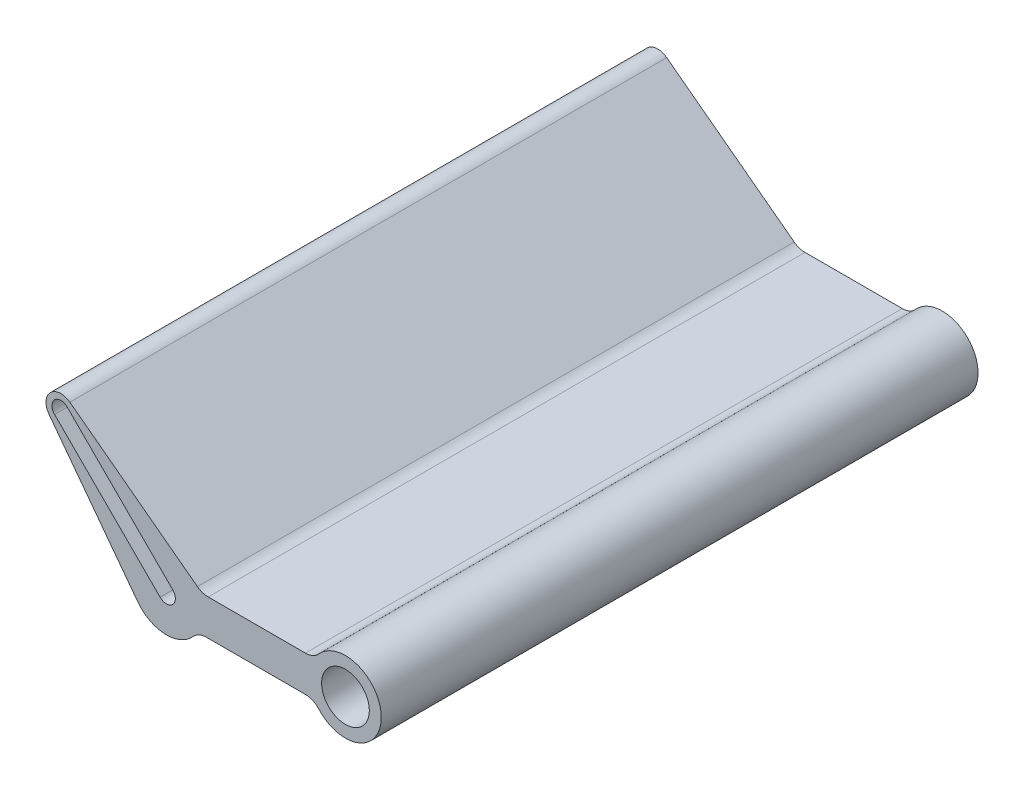
SolidWorks part; units mm, degrees
ref_plane "Front Plane" through (0, 0, 0) normal (0, 0, 1) x (1, 0, 0)
ref_plane "Top Plane" through (0, 0, 0) normal (0, 1, 0) x (1, 0, 0)
ref_plane "Right Plane" through (0, 0, 0) normal (1, 0, 0) x (0, 0, -1)
sketch "Sketch13" plane through (0, 0, 0) normal (0, 0, 1) x (1, 0, 0)
  line L0 (0, 0) -> (-176.7767, 176.7767) construction
  line L1 (-176.7767, 176.7767) -> (0, 0) construction
  line L2 (0, 0) -> (300, 0) construction
  line L3 (51.918, 36.0259) -> (-161.748, 196.7551)
  line L4 (-47.9483, -36.0689) -> (-196.7551, 161.748)
  line L5 (0, 0) -> (-176.7767, 176.7767) construction
  line L6 (69.9524, 30) -> (232.918, 30)
  line L7 (-10.6066, -10.6066) -> (-187.3833, 166.1701)
  line L8 (67.082, -30) -> (232.918, -30)
  line L9 (10.6066, 10.6066) -> (-166.1701, 187.3833)
  arc A0 (-161.748, 196.7551) -> (-196.7551, 161.748) centre (-176.7767, 176.7767) ccw
  arc A1 (-47.9483, -36.0689) -> (44.7214, -40) centre (0, 0) ccw
  arc A2 (255.2786, -40) -> (255.2786, 40) centre (300, 0) ccw
  arc A3 (-10.6066, -10.6066) -> (10.6066, 10.6066) centre (0, 0) ccw
  arc A4 (-166.1701, 187.3833) -> (-187.3833, 166.1701) centre (-176.7767, 176.7767) ccw
  circle A5 centre (300, 0) radius 40
  arc A6 (232.918, 30) -> (255.2786, 40) centre (232.918, 60) ccw
  arc A7 (255.2786, -40) -> (232.918, -30) centre (232.918, -60) ccw
  arc A8 (67.082, -30) -> (44.7214, -40) centre (67.082, -60) ccw
  arc A9 (51.918, 36.0259) -> (69.9524, 30) centre (69.9524, 60) ccw
  point P8 (-88.3883, 88.3883)
  point P11 (150, 0)
  point P14 (150, -30)
  dimension "D4" = 50
  dimension "D5" = 120
  dimension "D6" = 120
  dimension "D10" = 20
  dimension "D11" = 30
  dimension "D12" = 30
  dimension "D13" = 30
  dimension "D14" = 30
  dimension "D1" = 300
  dimension "D2" = 250
  dimension "D3" = 135
  dimension "D7" = 60
  dimension "D8" = 30
  dimension "D9" = 30
extrude "Boss-Extrude1" add sketch "Sketch13" along normal blind 1000
